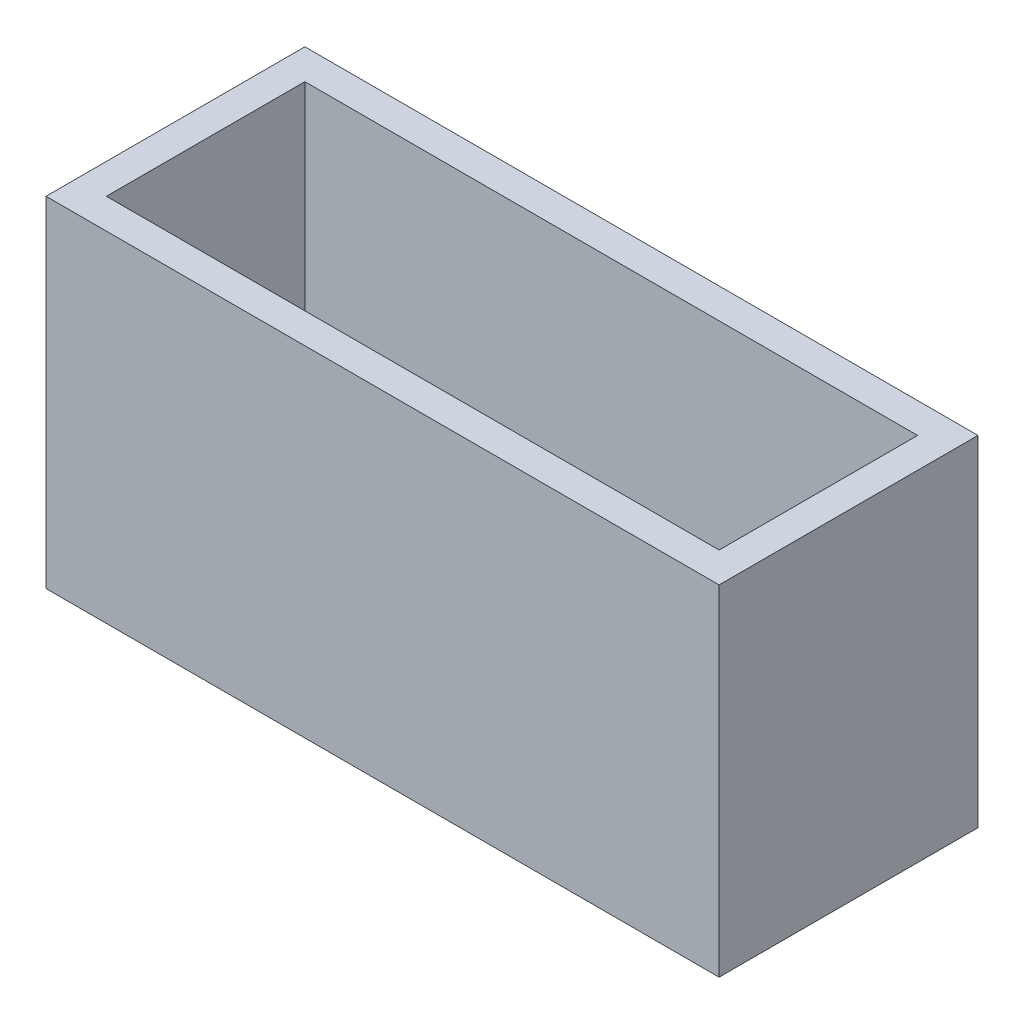
SolidWorks part; units mm, degrees
ref_plane "Front Plane" through (0, 0, 0) normal (0, 0, 1) x (1, 0, 0)
ref_plane "Top Plane" through (0, 0, 0) normal (0, 1, 0) x (1, 0, 0)
ref_plane "Right Plane" through (0, 0, 0) normal (1, 0, 0) x (0, 0, -1)
sketch "Sketch1" plane through (0, 0, 0) normal (0, 1, 0) x (1, 0, 0)
  line L0 (-901.7, 292.1) -> (901.7, 292.1)
  line L1 (-990.6, 381) -> (990.6, 381)
  line L2 (-990.6, 381) -> (-990.6, -381)
  line L3 (-990.6, -381) -> (990.6, -381)
  line L4 (990.6, 381) -> (990.6, -381)
  line L5 (-990.6, 381) -> (990.6, -381) construction
  line L6 (-990.6, -381) -> (990.6, 381) construction
  line L7 (901.7, 292.1) -> (901.7, -292.1)
  line L8 (-901.7, -292.1) -> (901.7, -292.1)
  line L9 (-901.7, 292.1) -> (-901.7, -292.1)
  point P0 (0, 0)
  dimension "D1" = 1981.2
  dimension "D2" = 762
  dimension "D3" = 88.9
extrude "Boss-Extrude1" add sketch "Sketch1" along normal blind 1000
